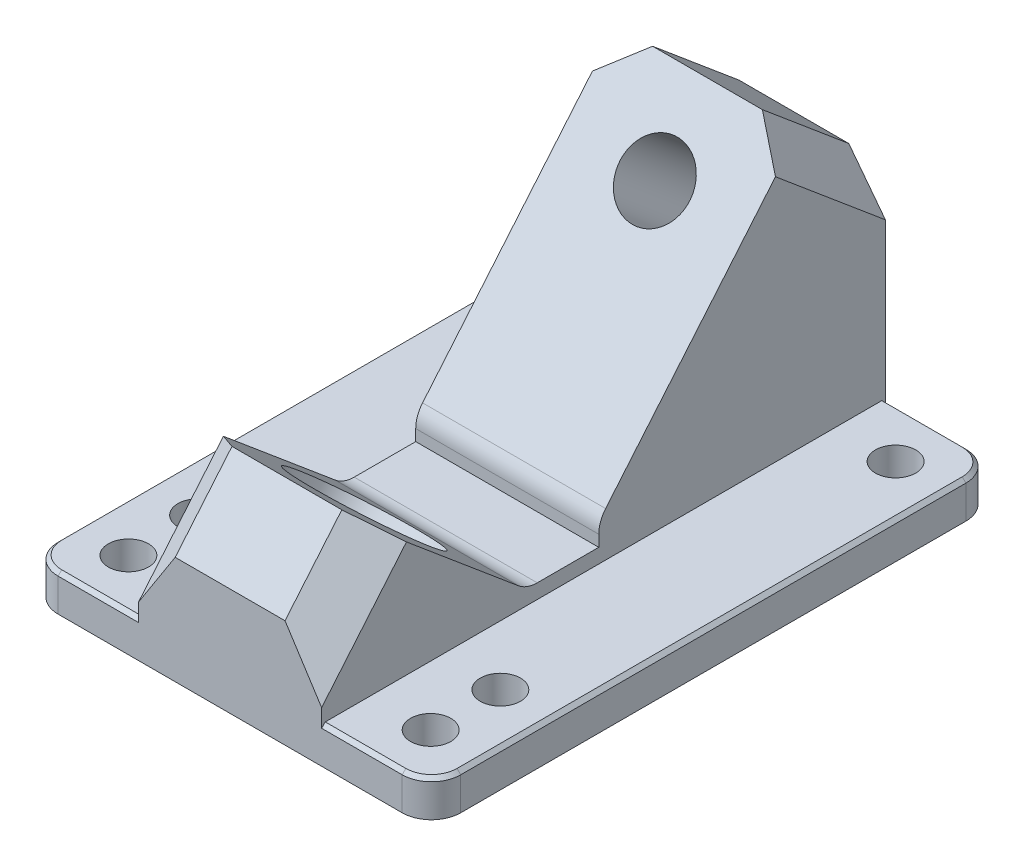
SolidWorks part; units mm, degrees
ref_plane "Front Plane" through (0, 0, 0) normal (0, 0, 1) x (1, 0, 0)
ref_plane "Top Plane" through (0, 0, 0) normal (0, 1, 0) x (1, 0, 0)
ref_plane "Right Plane" through (0, 0, 0) normal (1, 0, 0) x (0, 0, -1)
sketch "Sketch1" plane through (0, 0, 0) normal (0, 1, 0) x (1, 0, 0)
  line L0 (0, -39.5) -> (0, 38.5) construction
  line L1 (0, 0) -> (-27.5, 0) construction
  line L2 (27.5, 38.5) -> (27.5, -38.5)
  line L3 (-27.5, 38.5) -> (27.5, 38.5)
  line L4 (-27.5, 38.5) -> (-27.5, -38.5)
  line L5 (-27.5, -38.5) -> (27.5, -38.5)
  point P10 (27.5, 0)
  dimension "D1" = 38.5
  dimension "D3" = 27.5
extrude "Boss-Extrude1" add sketch "Sketch1" along normal blind 45
sketch "Sketch2" plane through (0, 0, 0) normal (0, 0, 1) x (1, 0, 0)
  line L0 (0, 0) -> (0, 45) construction
  line L1 (-27.5, 0) -> (27.5, 0) construction
  line L3 (-12.5, 45) -> (-12.5, 0)
  line L4 (-12.5, 45) -> (-27.5, 45)
  line L5 (-27.5, 45) -> (-27.5, 0)
  line L6 (-27.5, 0) -> (-12.5, 0)
  line L8 (27.5, 0) -> (12.5, 0)
  line L9 (27.5, 45) -> (27.5, 0)
  line L10 (12.5, 45) -> (12.5, 0)
  line L11 (12.5, 45) -> (27.5, 45)
  line L13 (-27.5, 45) -> (27.5, 45) construction
  dimension "D1" = 12.5
extrude "Cut-Extrude1" cut sketch "Sketch2" against normal through all and the other way through all contours L5 L6 L3 L4 | L10 L8 L9 L11
sketch "Sketch3" plane through (0, 0, 0) normal (1, 0, 0) x (0, 0, -1)
  line L0 (38.5, 6) -> (-38.5, 6) construction
  line L1 (-38.5, 15) -> (-31.5106, 23.3297)
  line L2 (-0.6503, 10.26) -> (26.6983, 42.8528)
  line L3 (38.5, 0) -> (-38.5, 0) construction
  line L4 (-5.0103, 10.26) -> (-0.6503, 10.26) construction
  line L5 (-38.5, 7.26) -> (-12.3594, 7.26) construction
  line L6 (38.5, 45) -> (38.5, 0) construction
  line L7 (38.5, 45) -> (-38.5, 45) construction
  line L8 (-31.5106, 23.3297) -> (-12.3594, 7.26) construction
  line L9 (-0.6503, 7.26) -> (-10.5081, 7.26)
  line L10 (-0.6503, 7.26) -> (-0.6503, 10.26)
  line L11 (26.6983, 42.8528) -> (38.5, 32.95)
  line L12 (-38.5, 15) -> (-38.5, 45)
  line L13 (-38.5, 45) -> (24.14, 45)
  line L14 (38.5, 32.95) -> (38.5, 45)
  line L15 (38.5, 45) -> (24.14, 45)
  line L16 (38.5, 45) -> (38.5, 0) construction
  line L17 (24.14, 45) -> (-5.0103, 10.26) construction
  line L18 (-30.7456, 24.2413) -> (-10.5081, 7.26)
  line L19 (24.14, 45) -> (38.5, 45)
  line L20 (-10.5081, 7.26) -> (38.5, 7.26) construction
  line L21 (-38.5, 45) -> (-38.5, 0) construction
  line L23 (-31.5106, 23.3297) -> (-30.7456, 24.2413)
  line L25 (-38.5, 45) -> (-38.5, 0) construction
  line L26 (38.5, 45) -> (38.5, 0) construction
  dimension "D2" = 50
  dimension "D3" = 1.26
  dimension "D4" = 25
  dimension "D5" = 3
  dimension "D6" = 14.36
  dimension "D7" = 3.34
  dimension "D8" = 32.95
  dimension "D9" = 1.19
  dimension "D10" = 6
  dimension "D11" = 15
extrude "Cut-Extrude2" cut sketch "Sketch3" against normal through all and the other way through all
sketch "Sketch9" plane through (0, 4.5594, 5.4337) normal (0, 0.6428, 0.766) x (1, 0, 0)
  line L0 (0, 0) -> (0, 82.1066) construction
  line L2 (-12.5, 49.9885) -> (12.5, 49.9885) construction
  circle A0 centre (0, 38.807) radius 4.7625
  dimension "D1" = 9.525
  dimension "D2" = 11.1815
extrude "Cut-Extrude5" cut sketch "Sketch9" against normal through all
sketch "Sketch5" plane through (0, 0, 0) normal (1, 0, 0) x (0, 0, -1)
  line L0 (38.5, 0) -> (38.5, 30)
  line L1 (38.5, 32.95) -> (38.5, 0) construction
  line L2 (38.5, 30) -> (13.327, 0)
  line L3 (38.5, 0) -> (-38.5, 0) construction
  line L5 (13.327, 0) -> (38.5, 0)
  dimension "D1" = 30
  dimension "D3" = 50
extrude "Cut-Extrude4" cut sketch "Sketch5" against normal blind 7.5 and the other way blind 7.5
chamfer "Chamfer1" distance 5 angle 45 4 edges at (-12.5, 19.6206, 34.6228) (12.5, 19.6206, 34.6228) (-12.5, 37.9014, -32.5992) (12.5, 37.9014, -32.5992)
fillet "Fillet1" radius 4 2 edges at (0, 10.26, 0.6503) (0, 7.26, 10.5081)
hole_wizard "Ø12.0mm Dowel Hole2" positions "Sketch15" profile "Sketch14" hole size "Ø12.0" standard "ANSI Metric"
sketch "Sketch15" plane through (0, -0.9139, 0.7669) normal (0, 0.766, -0.6428) x (1, 0, 0)
  line L0 (0, 0) -> (0, -56.9743) construction
  line L2 (-7.5, -39.1345) -> (7.5, -39.1345) construction
  point P0 (0, -25.3331)
  dimension "D1" = 13.8014
sketch "Sketch14" plane through (0, 15.3699, 20.1732) normal (1, 0, 0) x (0, 0.6428, 0.766)
  line L0 (0, 0) -> (0, 17.4077)
  line L1 (0, 17.4077) -> (9, 12)
  line L2 (9, 12) -> (9, 0)
  line L5 (9, 0) -> (0, 0)
  line L10 (0, 17.4077) -> (-9, 12) construction
  line L11 (0, 0) -> (0, 107.95) construction
  dimension "Hole Dia." = 18
  dimension "Hole Depth" = 12
  dimension "Drill Angle" = 118
sketch "Sketch16" plane through (0, 0, 0) normal (1, 0, 0) x (0, 0, -1)
  line L0 (-38.5, 0.28) -> (38.5, 0.28)
  line L2 (38.5, 26.423) -> (38.5, 0) construction
  line L3 (-38.5, 7.2214) -> (-38.5, 0) construction
  line L4 (-38.5, 0.28) -> (-38.5, 0)
  line L5 (-38.5, 0) -> (38.5, 0)
  line L6 (38.5, 0) -> (38.5, 0.28)
  dimension "D1" = 0.28
extrude "Cut-Extrude6" cut sketch "Sketch16" against normal through all and the other way through all
sketch "Sketch17" plane through (0, 0.28, 0) normal (0, -1, 0) x (1, 0, 0)
  line L0 (0, -53.2285) -> (0, 59.0492) construction
  line L1 (0, 0) -> (-40.4384, 0) construction
  line L2 (-27.5, -38.5) -> (-12.5, -38.5)
  line L3 (-27.5, -38.5) -> (-27.5, 38.5)
  line L4 (12.5, -38.5) -> (12.5, 38.5)
  line L5 (-27.5, 38.5) -> (-12.5, 38.5)
  line L6 (-12.5, -38.5) -> (-12.5, 38.5)
  line L7 (27.5, 38.5) -> (12.5, 38.5)
  line L8 (27.5, -38.5) -> (27.5, 38.5)
  line L9 (27.5, -38.5) -> (12.5, -38.5)
  point P11 (-27.5, 0)
  point P12 (27.5, 0)
  dimension "D1" = 15
extrude "Boss-Extrude2" add sketch "Sketch17" against normal blind 5
sketch "Sketch18" plane through (0, 0, 0) normal (0, 1, 0) x (1, 0, 0)
  line L0 (0, 47.1015) -> (0, -50.3182) construction
  line L1 (-20.64, -50.3182) -> (-20.64, 47.1015) construction
  line L2 (-12.5, -38.5) -> (-27.5, -38.5) construction
  line L4 (20.64, -50.3182) -> (20.64, 47.1015) construction
  circle A0 centre (-20.64, -31.75) radius 2.75
  circle A1 centre (-20.64, 31.75) radius 2.75
  circle A2 centre (-20.64, -22.23) radius 2.75
  circle A3 centre (20.64, -22.23) radius 2.75
  circle A4 centre (20.64, 31.75) radius 2.75
  circle A5 centre (20.64, -31.75) radius 2.75
  dimension "D1" = 5.5
  dimension "D2" = 20.64
  dimension "D3" = 6.75
  dimension "D4" = 63.5
  dimension "D5" = 53.98
extrude "Cut-Extrude8" cut sketch "Sketch18" along normal blind 10
fillet "Fillet2" radius 4 4 edges at (27.5, 2.78, -38.5) (27.5, 2.78, 38.5) (-27.5, 2.78, -38.5) (-27.5, 2.78, 38.5)
chamfer "Chamfer2" distance 0.5 angle 45 15 edges at (-7.5, 15.14, -38.5) (-7.5, 0.28, -26.031) (0, 0.28, -13.562) (7.5, 0.28, -26.031) (7.5, 15.14, -38.5) (-26.3284, 5.28, -37.3284) (-27.5, 5.28, 0) (-26.3284, 5.28, 37.3284) (26.3284, 5.28, -37.3284) (27.5, 5.28, 0) (26.3284, 5.28, 37.3284)
